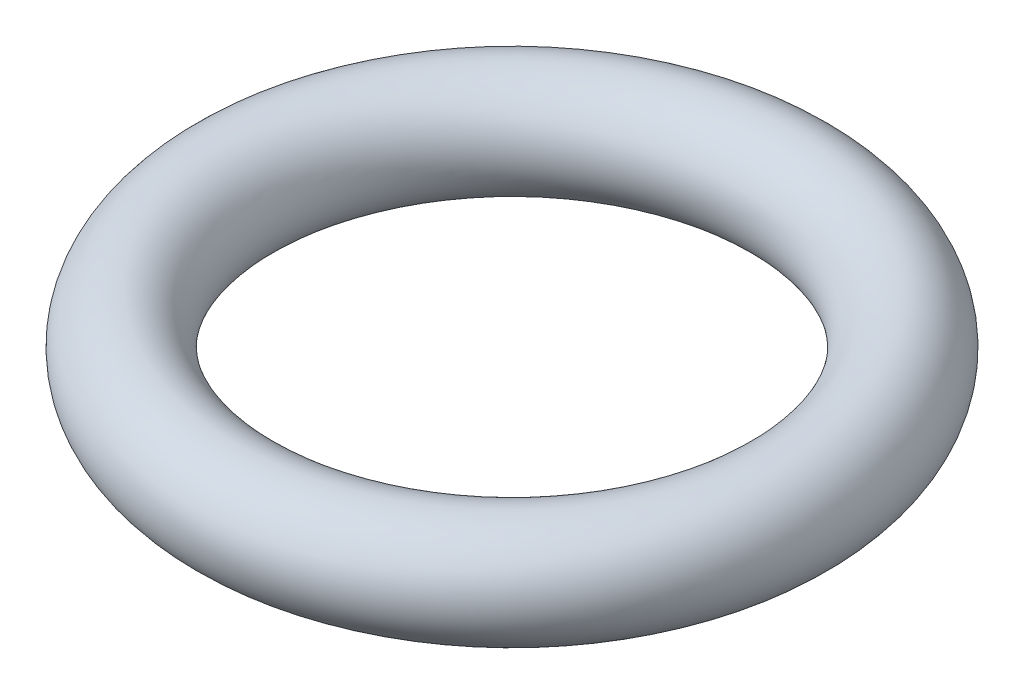
SolidWorks part; units mm, degrees
ref_plane "Front Plane" through (0, 0, 0) normal (0, 0, 1) x (1, 0, 0)
ref_plane "Top Plane" through (0, 0, 0) normal (0, 1, 0) x (1, 0, 0)
ref_plane "Right Plane" through (0, 0, 0) normal (1, 0, 0) x (0, 0, -1)
sketch "Sketch1" plane through (0, 0, 0) normal (0, 1, 0) x (1, 0, 0)
  circle A0 centre (0, 0) radius 11.645
  dimension "D1" = 23.29
sketch "Sketch2" plane through (0, 0, 0) normal (1, 0, 0) x (0, 0, -1)
  circle A0 centre (-11.645, 0) radius 2.24
  dimension "D1" = 4.48
sweep "Sweep1" add profiles "Sketch2" path "Sketch1"
equation "\"D1@Sketch1\"=18.81+4.48"
